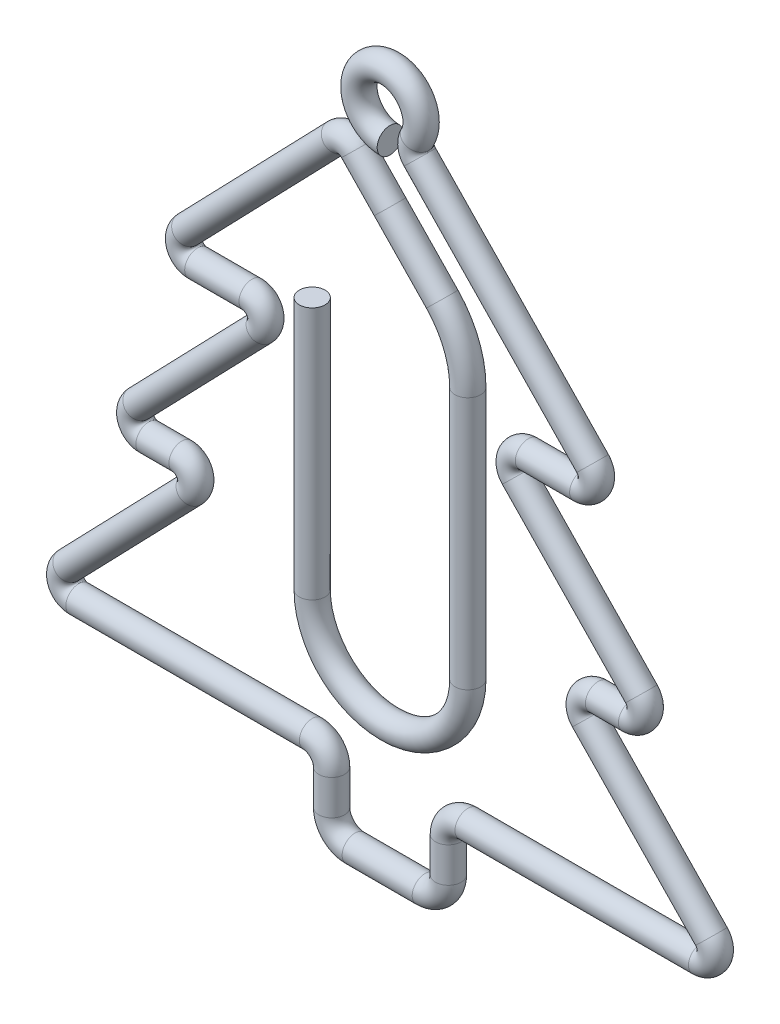
SolidWorks part; units mm, degrees
ref_plane "Спереди" through (0, 0, 0) normal (0, 0, 1) x (1, 0, 0)
ref_plane "Сверху" through (0, 0, 0) normal (0, 1, 0) x (1, 0, 0)
ref_plane "Справа" through (0, 0, 0) normal (1, 0, 0) x (0, 0, -1)
sketch "Эскиз1" plane through (0, 0, 0) normal (0, 0, 1) x (1, 0, 0)
  line L0 (7.6602, -7.9323) -> (52.0499, -53.8992)
  line L1 (0, 31.2797) -> (0, -228.5698) construction
  line L2 (49.4603, -60) -> (35.5061, -60)
  line L3 (32.9165, -66.1008) -> (64.5896, -98.8992)
  line L4 (62, -105) -> (53.5061, -105)
  line L5 (50.9165, -111.1008) -> (82.5896, -143.8992)
  line L6 (80, -150) -> (20, -150)
  line L7 (15, -155) -> (15, -164)
  line L8 (9, -170) -> (-9, -170)
  line L9 (-49.4603, -60) -> (-35.5061, -60)
  line L10 (-32.9165, -66.1008) -> (-64.5896, -98.8992)
  line L11 (-62, -105) -> (-53.5061, -105)
  line L12 (-50.9165, -111.1008) -> (-82.5896, -143.8992)
  line L13 (-80, -150) -> (-20, -150)
  line L14 (-15, -155) -> (-15, -164)
  line L15 (0, -22.7817) -> (13.3954, -36.653)
  line L16 (20, -53) -> (20, -118)
  line L17 (-13.5896, -14.0725) -> (-52.0499, -53.8992)
  line L18 (-20, -53) -> (-20, -118)
  line L19 (0, -22.7817) -> (-8.4104, -14.0725)
  arc A0 (0, -8) -> (7.0688, -3.7459) centre (0, 0) cw
  arc A1 (13.3954, -36.653) -> (20, -53) centre (-3.5324, -53) cw
  arc A2 (20, -118) -> (-20, -118) centre (0, -118) cw
  arc A3 (49.4603, -60) -> (52.0499, -53.8992) centre (49.4603, -56.4) ccw
  arc A4 (62, -105) -> (64.5896, -98.8992) centre (62, -101.4) ccw
  arc A5 (80, -150) -> (82.5896, -143.8992) centre (80, -146.4) ccw
  arc A6 (15, -164) -> (9, -170) centre (9, -164) cw
  arc A7 (-49.4603, -60) -> (-52.0499, -53.8992) centre (-49.4603, -56.4) cw
  arc A8 (-62, -105) -> (-64.5896, -98.8992) centre (-62, -101.4) cw
  arc A9 (-80, -150) -> (-82.5896, -143.8992) centre (-80, -146.4) cw
  arc A10 (-15, -164) -> (-9, -170) centre (-9, -164) ccw
  arc A11 (53.5061, -105) -> (50.9165, -111.1008) centre (53.5061, -108.6) ccw
  arc A12 (35.5061, -60) -> (32.9165, -66.1008) centre (35.5061, -63.6) ccw
  arc A13 (-35.5061, -60) -> (-32.9165, -66.1008) centre (-35.5061, -63.6) cw
  arc A14 (-53.5061, -105) -> (-50.9165, -111.1008) centre (-53.5061, -108.6) cw
  arc A15 (-13.5896, -14.0725) -> (-8.4104, -14.0725) centre (-11, -16.5732) cw
  arc A16 (7.0688, -3.7459) -> (7.6602, -7.9323) centre (10.2498, -5.4316) ccw
  arc A17 (20, -150) -> (15, -155) centre (20, -155) ccw
  arc A18 (-20, -150) -> (-15, -155) centre (-20, -155) cw
  point P22 (0, -160)
  point P48 (0, -170)
  dimension "D6" = 8
  dimension "D7" = 20
  dimension "D12" = 11
  dimension "D13" = 3.6
  dimension "D14" = 6
  dimension "D16" = 5
  dimension "D1" = 44
  dimension "D2" = 9
  dimension "D3" = 45
  dimension "D4" = 45
  dimension "D5" = 170
  dimension "D8" = 118
  dimension "D9" = 65
  dimension "D10" = 60
  dimension "D11" = 80
  dimension "D15" = 62
ref_plane "Плоскость1" through (0, -8, 0) normal (-1, 0, 0) x (0, 0, 1)
sketch "Эскиз2" plane through (0, -8, 0) normal (-1, 0, 0) x (0, 0, 1)
  circle A0 centre (0, 0) radius 3.3
  dimension "D1" = 6.6
sweep "По траектории4" add profiles "Эскиз2" path "Эскиз1"
